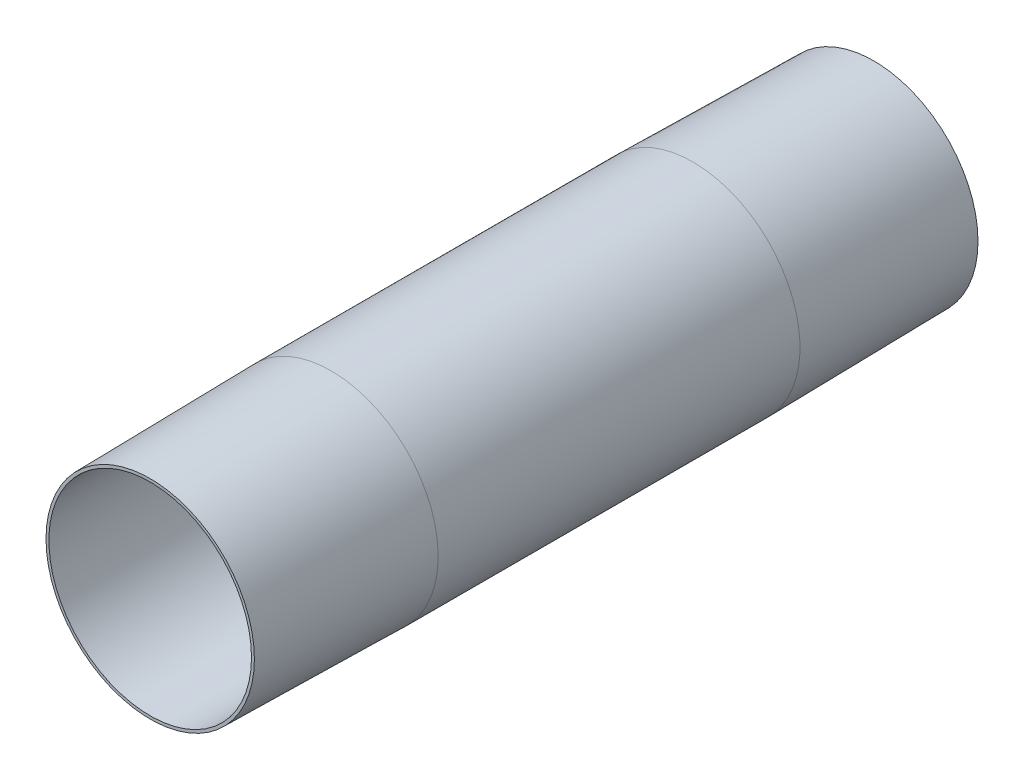
SolidWorks part; units mm, degrees
ref_plane "Ön Düzlem" through (0, 0, 0) normal (0, 0, 1) x (1, 0, 0)
ref_plane "Üst Düzlem" through (0, 0, 0) normal (0, 1, 0) x (1, 0, 0)
ref_plane "Sağ Düzlem" through (0, 0, 0) normal (1, 0, 0) x (0, 0, -1)
sketch "Çizim1" plane through (0, 0, 0) normal (0, 0, 1) x (1, 0, 0)
  circle A0 centre (0, 0) radius 70
  circle A1 centre (0, 0) radius 74
  dimension "D1" = 140
  dimension "D2" = 148
extrude "Yükseklik-Ekstrüzyon1" add sketch "Çizim1" along normal blind 500
sketch "Çizim2" plane through (0, 0, 0) normal (0, 1, 0) x (1, 0, 0)
  line L0 (0, 0) -> (0, -500) construction
  line L1 (-70, -500) -> (70, -500) construction
  line L6 (-74, -500) -> (-72, -500)
  line L7 (-74, -500) -> (74, -500) construction
  line L8 (-72, -500) -> (-74, -375)
  line L9 (-74, -375) -> (-74, -500)
  line L10 (-74, 0) -> (-74, -500) construction
  line L11 (-74, -125) -> (-74, 0)
  line L12 (74, 0) -> (-74, 0) construction
  line L13 (-74, 0) -> (-72, 0)
  line L14 (-72, 0) -> (-74, -125)
  dimension "D1" = 2
  dimension "D2" = 125
  dimension "D3" = 2
  dimension "D4" = 125
revolve "Kes-Döndür1" cut sketch "Çizim2" angle 360 about L0
